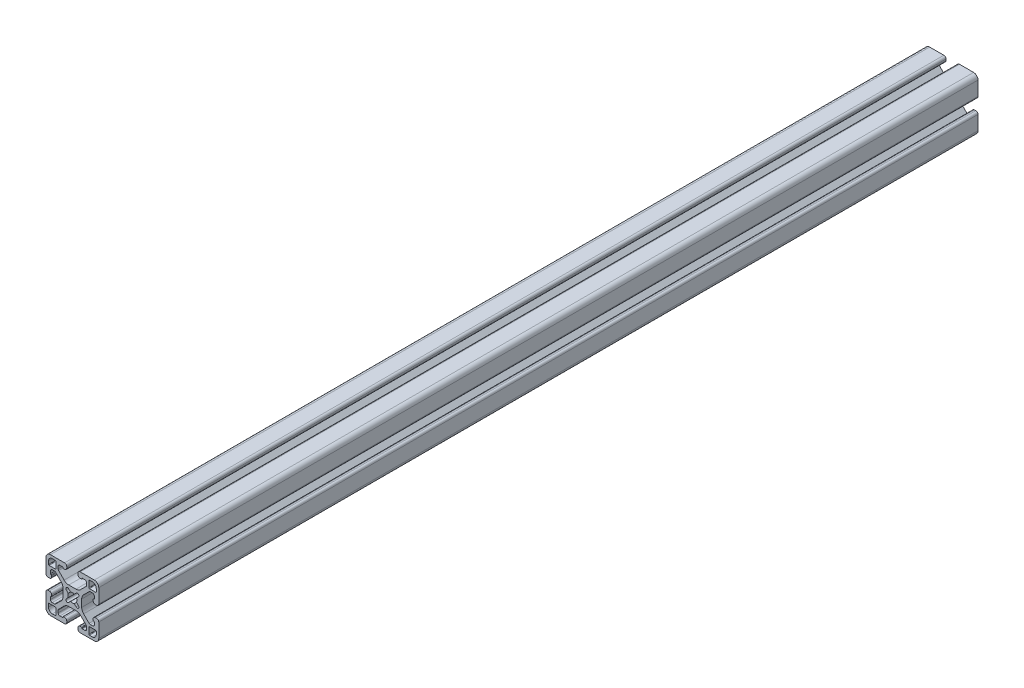
SolidWorks part; units mm, degrees
ref_plane "Front Plane" through (0, 0, 0) normal (0, 0, 1) x (1, 0, 0)
ref_plane "Top Plane" through (0, 0, 0) normal (0, 1, 0) x (1, 0, 0)
ref_plane "Right Plane" through (0, 0, 0) normal (1, 0, 0) x (0, 0, -1)
sketch "Sketch1" plane through (0, 0, 0) normal (0, 0, 1) x (1, 0, 0)
  line L0 (-66.7042, -2.4885) -> (-65.3338, -1.1181)
  line L1 (-65.3338, 1.5948) -> (-66.7042, 2.9652)
  line L2 (-65.0878, 4.5817) -> (-63.7174, 3.2113)
  line L3 (-61.0045, 3.2113) -> (-59.7212, 4.484)
  line L4 (-58.1153, 2.8781) -> (-59.3881, 1.5948)
  line L5 (-59.3881, -1.1181) -> (-58.0176, -2.4885)
  line L6 (-59.6341, -4.1049) -> (-61.0045, -2.7345)
  line L7 (-63.7174, -2.7345) -> (-65.0878, -4.1049)
  line L8 (-79.6075, 12.4812) -> (-79.6075, 14.691)
  line L9 (-76.8135, 17.485) -> (-74.6037, 17.485)
  line L10 (-74.2227, 17.104) -> (-74.2227, 12.4812)
  line L11 (-74.6037, 12.1002) -> (-79.2265, 12.1002)
  line L12 (-74.6037, -17.0082) -> (-76.8135, -17.0082)
  line L13 (-79.6075, -14.2142) -> (-79.6075, -12.0044)
  line L14 (-79.2265, -11.6234) -> (-74.6037, -11.6234)
  line L15 (-74.2227, -12.0044) -> (-74.2227, -16.6272)
  line L16 (-45.1143, -12.0044) -> (-45.1143, -14.2142)
  line L17 (-47.9083, -17.0082) -> (-50.1181, -17.0082)
  line L18 (-50.4991, -16.6272) -> (-50.4991, -12.0044)
  line L19 (-50.1181, -11.6234) -> (-45.4953, -11.6234)
  line L20 (-50.1181, 17.485) -> (-47.9083, 17.485)
  line L21 (-45.1143, 14.691) -> (-45.1143, 12.4812)
  line L22 (-45.4953, 12.1002) -> (-50.1181, 12.1002)
  line L23 (-50.4991, 12.4812) -> (-50.4991, 17.104)
  line L24 (-46.5368, -7.0006) -> (-46.5368, -8.7746)
  line L25 (-47.8067, -10.0486) -> (-49.3926, -10.0486)
  line L26 (-50.2907, -9.6767) -> (-54.2388, -5.7286)
  line L27 (-55.6299, -2.3699) -> (-55.6299, 2.8467)
  line L28 (-54.2388, 6.2053) -> (-50.2907, 10.1534)
  line L29 (-49.3926, 10.5254) -> (-47.8067, 10.5254)
  line L30 (-46.5368, 9.2513) -> (-46.5368, 7.4774)
  line L31 (-46.9178, 7.0964) -> (-46.994, 7.0964)
  line L32 (-47.375, 6.7154) -> (-47.3749, 5.8772)
  line L33 (-45.8001, 4.3024) -> (-44.8857, 4.3024)
  line L34 (-43.3109, 5.8772) -> (-43.3109, 16.1134)
  line L35 (-46.4859, 19.2884) -> (-56.7221, 19.2884)
  line L36 (-58.2969, 17.7136) -> (-58.2969, 16.7992)
  line L37 (-56.7222, 15.2244) -> (-55.884, 15.2244)
  line L38 (-55.503, 15.6054) -> (-55.503, 15.6816)
  line L39 (-55.122, 16.0626) -> (-53.348, 16.0626)
  line L40 (-52.0739, 14.7926) -> (-52.0739, 13.2067)
  line L41 (-52.4459, 12.3087) -> (-56.394, 8.3606)
  line L42 (-59.7526, 6.9694) -> (-64.9693, 6.9694)
  line L43 (-68.3279, 8.3606) -> (-72.276, 12.3087)
  line L44 (-72.6479, 13.2067) -> (-72.6479, 14.7926)
  line L45 (-71.3739, 16.0626) -> (-69.5999, 16.0626)
  line L46 (-69.2189, 15.6816) -> (-69.2189, 15.6054)
  line L47 (-68.8379, 15.2244) -> (-67.9997, 15.2244)
  line L48 (-66.4249, 16.7992) -> (-66.4249, 17.7136)
  line L49 (-67.9997, 19.2884) -> (-78.2359, 19.2884)
  line L50 (-81.4109, 16.1134) -> (-81.4109, 5.8772)
  line L51 (-79.8361, 4.3024) -> (-78.9217, 4.3024)
  line L52 (-77.3469, 5.8772) -> (-77.3469, 6.7154)
  line L53 (-77.7279, 7.0964) -> (-77.8041, 7.0964)
  line L54 (-78.1851, 7.4774) -> (-78.1851, 9.2513)
  line L55 (-76.9151, 10.5254) -> (-75.3293, 10.5254)
  line L56 (-74.4312, 10.1534) -> (-70.4831, 6.2053)
  line L57 (-69.0919, 2.8467) -> (-69.0919, -2.3699)
  line L58 (-70.4831, -5.7286) -> (-74.4312, -9.6767)
  line L59 (-75.3293, -10.0486) -> (-76.9151, -10.0486)
  line L60 (-78.1851, -8.7746) -> (-78.1851, -7.0006)
  line L61 (-77.8041, -6.6196) -> (-77.7279, -6.6196)
  line L62 (-77.3469, -6.2386) -> (-77.3469, -5.4004)
  line L63 (-78.9217, -3.8256) -> (-79.8361, -3.8256)
  line L64 (-81.4109, -5.4004) -> (-81.4109, -15.6366)
  line L65 (-78.2359, -18.8116) -> (-67.9997, -18.8116)
  line L66 (-66.4249, -17.2368) -> (-66.4249, -16.3224)
  line L67 (-67.9997, -14.7476) -> (-68.8379, -14.7476)
  line L68 (-69.2189, -15.1286) -> (-69.2189, -15.2048)
  line L69 (-69.5999, -15.5858) -> (-71.3739, -15.5858)
  line L70 (-72.6479, -14.3158) -> (-72.6479, -12.7299)
  line L71 (-72.276, -11.8319) -> (-68.3279, -7.8838)
  line L72 (-64.9693, -6.4926) -> (-59.7526, -6.4926)
  line L73 (-56.394, -7.8838) -> (-52.4459, -11.8319)
  line L74 (-52.0739, -12.7299) -> (-52.0739, -14.3158)
  line L75 (-53.348, -15.5858) -> (-55.122, -15.5858)
  line L76 (-55.503, -15.2048) -> (-55.503, -15.1286)
  line L77 (-55.884, -14.7476) -> (-56.7222, -14.7476)
  line L78 (-58.2969, -16.3224) -> (-58.2969, -17.2368)
  line L79 (-56.7221, -18.8116) -> (-46.4859, -18.8116)
  line L80 (-43.3109, -15.6366) -> (-43.3109, -5.4004)
  line L81 (-44.8857, -3.8256) -> (-45.8001, -3.8256)
  line L82 (-47.3749, -5.4004) -> (-47.375, -6.2386)
  line L83 (-46.994, -6.6196) -> (-46.9178, -6.6196)
  arc A0 (-66.7042, -2.4885) -> (-65.0878, -4.1049) centre (-65.896, -3.2967) ccw
  arc A1 (-65.3338, 1.5948) -> (-65.3338, -1.1181) centre (-62.3609, 0.2384) ccw
  arc A2 (-65.0878, 4.5817) -> (-66.7042, 2.9652) centre (-65.896, 3.7734) ccw
  arc A3 (-61.0045, 3.2113) -> (-63.7174, 3.2113) centre (-62.3609, 0.2384) ccw
  arc A4 (-58.1153, 2.8781) -> (-59.7212, 4.484) centre (-58.8259, 3.7734) ccw
  arc A5 (-59.3881, -1.1181) -> (-59.3881, 1.5948) centre (-62.3609, 0.2384) ccw
  arc A6 (-59.6341, -4.1049) -> (-58.0176, -2.4885) centre (-58.8259, -3.2967) ccw
  arc A7 (-63.7174, -2.7345) -> (-61.0045, -2.7345) centre (-62.3609, 0.2384) ccw
  arc A8 (-79.6075, 12.4812) -> (-79.2265, 12.1002) centre (-79.2265, 12.4812) ccw
  arc A9 (-76.8135, 17.485) -> (-79.6075, 14.691) centre (-76.8135, 14.691) ccw
  arc A10 (-74.2227, 17.104) -> (-74.6037, 17.485) centre (-74.6037, 17.104) ccw
  arc A11 (-74.6037, 12.1002) -> (-74.2227, 12.4812) centre (-74.6037, 12.4812) ccw
  arc A12 (-74.6037, -17.0082) -> (-74.2227, -16.6272) centre (-74.6037, -16.6272) ccw
  arc A13 (-79.6075, -14.2142) -> (-76.8135, -17.0082) centre (-76.8135, -14.2142) ccw
  arc A14 (-79.2265, -11.6234) -> (-79.6075, -12.0044) centre (-79.2265, -12.0044) ccw
  arc A15 (-74.2227, -12.0044) -> (-74.6037, -11.6234) centre (-74.6037, -12.0044) ccw
  arc A16 (-45.1143, -12.0044) -> (-45.4953, -11.6234) centre (-45.4953, -12.0044) ccw
  arc A17 (-47.9083, -17.0082) -> (-45.1143, -14.2142) centre (-47.9083, -14.2142) ccw
  arc A18 (-50.4991, -16.6272) -> (-50.1181, -17.0082) centre (-50.1181, -16.6272) ccw
  arc A19 (-50.1181, -11.6234) -> (-50.4991, -12.0044) centre (-50.1181, -12.0044) ccw
  arc A20 (-50.1181, 17.485) -> (-50.4991, 17.104) centre (-50.1181, 17.104) ccw
  arc A21 (-45.1143, 14.691) -> (-47.9083, 17.485) centre (-47.9083, 14.691) ccw
  arc A22 (-45.4953, 12.1002) -> (-45.1143, 12.4812) centre (-45.4953, 12.4812) ccw
  arc A23 (-50.4991, 12.4812) -> (-50.1181, 12.1002) centre (-50.1181, 12.4812) ccw
  arc A24 (-47.8067, -10.0486) -> (-46.5368, -8.7746) centre (-47.8067, -8.7786) ccw
  arc A25 (-50.2907, -9.6767) -> (-49.3926, -10.0486) centre (-49.3926, -8.7786) ccw
  arc A26 (-55.6299, -2.3699) -> (-54.2388, -5.7286) centre (-50.8801, -2.3699) ccw
  arc A27 (-54.2388, 6.2053) -> (-55.6299, 2.8467) centre (-50.8801, 2.8467) ccw
  arc A28 (-49.3926, 10.5254) -> (-50.2907, 10.1534) centre (-49.3926, 9.2554) ccw
  arc A29 (-46.5368, 9.2513) -> (-47.8067, 10.5254) centre (-47.8067, 9.2554) ccw
  arc A30 (-46.9178, 7.0964) -> (-46.5368, 7.4774) centre (-46.9178, 7.4774) ccw
  arc A31 (-46.994, 7.0964) -> (-47.375, 6.7154) centre (-46.994, 6.7154) ccw
  arc A32 (-47.3749, 5.8772) -> (-45.8001, 4.3024) centre (-45.8001, 5.8772) ccw
  arc A33 (-44.8857, 4.3024) -> (-43.3109, 5.8772) centre (-44.8857, 5.8772) ccw
  arc A34 (-43.3109, 16.1134) -> (-46.4859, 19.2884) centre (-46.4859, 16.1134) ccw
  arc A35 (-56.7221, 19.2884) -> (-58.2969, 17.7136) centre (-56.7221, 17.7136) ccw
  arc A36 (-58.2969, 16.7992) -> (-56.7222, 15.2244) centre (-56.7221, 16.7992) ccw
  arc A37 (-55.884, 15.2244) -> (-55.503, 15.6054) centre (-55.884, 15.6054) ccw
  arc A38 (-55.122, 16.0626) -> (-55.503, 15.6816) centre (-55.122, 15.6816) ccw
  arc A39 (-52.0739, 14.7926) -> (-53.348, 16.0626) centre (-53.3439, 14.7926) ccw
  arc A40 (-52.4459, 12.3087) -> (-52.0739, 13.2067) centre (-53.3439, 13.2067) ccw
  arc A41 (-59.7526, 6.9694) -> (-56.394, 8.3606) centre (-59.7526, 11.7192) ccw
  arc A42 (-68.3279, 8.3606) -> (-64.9693, 6.9694) centre (-64.9693, 11.7192) ccw
  arc A43 (-72.6479, 13.2067) -> (-72.276, 12.3087) centre (-71.3779, 13.2067) ccw
  arc A44 (-71.3739, 16.0626) -> (-72.6479, 14.7926) centre (-71.3779, 14.7926) ccw
  arc A45 (-69.2189, 15.6816) -> (-69.5999, 16.0626) centre (-69.5999, 15.6816) ccw
  arc A46 (-69.2189, 15.6054) -> (-68.8379, 15.2244) centre (-68.8379, 15.6054) ccw
  arc A47 (-67.9997, 15.2244) -> (-66.4249, 16.7992) centre (-67.9997, 16.7992) ccw
  arc A48 (-66.4249, 17.7136) -> (-67.9997, 19.2884) centre (-67.9997, 17.7136) ccw
  arc A49 (-78.2359, 19.2884) -> (-81.4109, 16.1134) centre (-78.2359, 16.1134) ccw
  arc A50 (-81.4109, 5.8772) -> (-79.8361, 4.3024) centre (-79.8361, 5.8772) ccw
  arc A51 (-78.9217, 4.3024) -> (-77.3469, 5.8772) centre (-78.9217, 5.8772) ccw
  arc A52 (-77.3469, 6.7154) -> (-77.7279, 7.0964) centre (-77.7279, 6.7154) ccw
  arc A53 (-78.1851, 7.4774) -> (-77.8041, 7.0964) centre (-77.8041, 7.4774) ccw
  arc A54 (-76.9151, 10.5254) -> (-78.1851, 9.2513) centre (-76.9151, 9.2554) ccw
  arc A55 (-74.4312, 10.1534) -> (-75.3293, 10.5254) centre (-75.3293, 9.2554) ccw
  arc A56 (-69.0919, 2.8467) -> (-70.4831, 6.2053) centre (-73.8417, 2.8467) ccw
  arc A57 (-70.4831, -5.7286) -> (-69.0919, -2.3699) centre (-73.8417, -2.3699) ccw
  arc A58 (-75.3293, -10.0486) -> (-74.4312, -9.6767) centre (-75.3293, -8.7786) ccw
  arc A59 (-78.1851, -8.7746) -> (-76.9151, -10.0486) centre (-76.9151, -8.7786) ccw
  arc A60 (-77.8041, -6.6196) -> (-78.1851, -7.0006) centre (-77.8041, -7.0006) ccw
  arc A61 (-77.7279, -6.6196) -> (-77.3469, -6.2386) centre (-77.7279, -6.2386) ccw
  arc A62 (-77.3469, -5.4004) -> (-78.9217, -3.8256) centre (-78.9217, -5.4004) ccw
  arc A63 (-79.8361, -3.8256) -> (-81.4109, -5.4004) centre (-79.8361, -5.4004) ccw
  arc A64 (-81.4109, -15.6366) -> (-78.2359, -18.8116) centre (-78.2359, -15.6366) ccw
  arc A65 (-67.9997, -18.8116) -> (-66.4249, -17.2368) centre (-67.9997, -17.2368) ccw
  arc A66 (-66.4249, -16.3224) -> (-67.9997, -14.7476) centre (-67.9997, -16.3224) ccw
  arc A67 (-68.8379, -14.7476) -> (-69.2189, -15.1286) centre (-68.8379, -15.1286) ccw
  arc A68 (-69.5999, -15.5858) -> (-69.2189, -15.2048) centre (-69.5999, -15.2048) ccw
  arc A69 (-72.6479, -14.3158) -> (-71.3739, -15.5858) centre (-71.3779, -14.3158) ccw
  arc A70 (-72.276, -11.8319) -> (-72.6479, -12.7299) centre (-71.3779, -12.7299) ccw
  arc A71 (-64.9693, -6.4926) -> (-68.3279, -7.8838) centre (-64.9693, -11.2424) ccw
  arc A72 (-56.394, -7.8838) -> (-59.7526, -6.4926) centre (-59.7526, -11.2424) ccw
  arc A73 (-52.0739, -12.7299) -> (-52.4459, -11.8319) centre (-53.3439, -12.7299) ccw
  arc A74 (-53.348, -15.5858) -> (-52.0739, -14.3158) centre (-53.3439, -14.3158) ccw
  arc A75 (-55.503, -15.2048) -> (-55.122, -15.5858) centre (-55.122, -15.2048) ccw
  arc A76 (-55.503, -15.1286) -> (-55.884, -14.7476) centre (-55.884, -15.1286) ccw
  arc A77 (-56.7222, -14.7476) -> (-58.2969, -16.3224) centre (-56.7221, -16.3224) ccw
  arc A78 (-58.2969, -17.2368) -> (-56.7221, -18.8116) centre (-56.7221, -17.2368) ccw
  arc A79 (-46.4859, -18.8116) -> (-43.3109, -15.6366) centre (-46.4859, -15.6366) ccw
  arc A80 (-43.3109, -5.4004) -> (-44.8857, -3.8256) centre (-44.8857, -5.4004) ccw
  arc A81 (-45.8001, -3.8256) -> (-47.3749, -5.4004) centre (-45.8001, -5.4004) ccw
  arc A82 (-47.375, -6.2386) -> (-46.994, -6.6196) centre (-46.994, -6.2386) ccw
  arc A83 (-46.5368, -7.0006) -> (-46.9178, -6.6196) centre (-46.9178, -7.0006) ccw
extrude "Extrude1" add sketch "Sketch1" against normal blind 635
